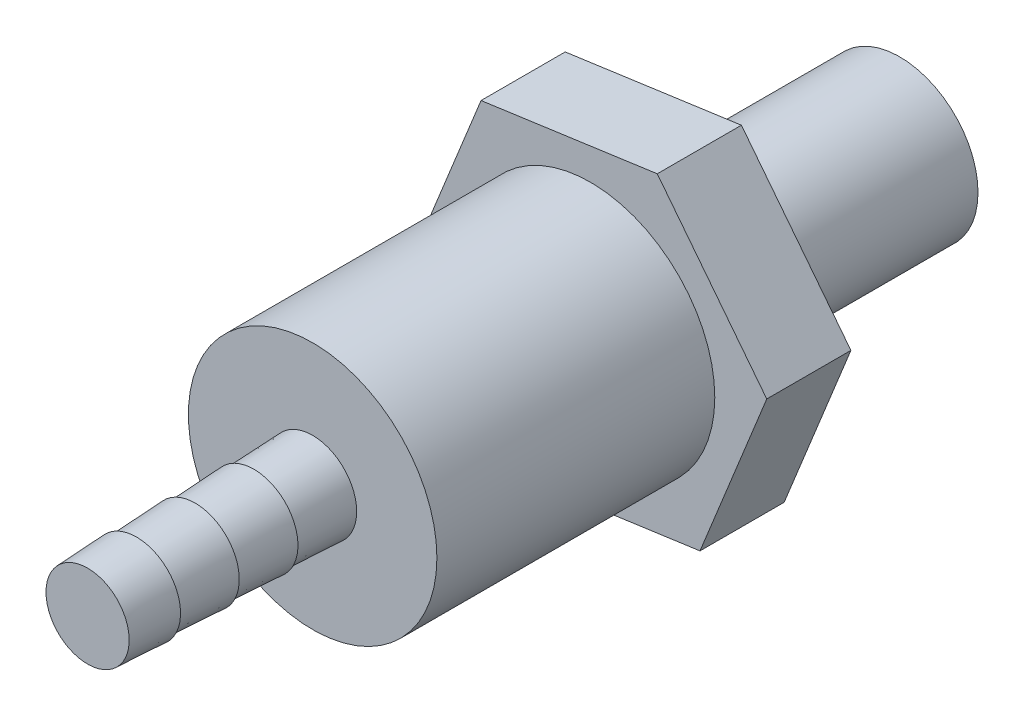
SolidWorks part; units mm, degrees
ref_plane "Face" through (0, 0, 0) normal (0, 0, 1) x (1, 0, 0)
ref_plane "Dessus" through (0, 0, 0) normal (0, 1, 0) x (1, 0, 0)
ref_plane "Droite" through (0, 0, 0) normal (1, 0, 0) x (0, 0, -1)
sketch "Esquisse1" plane through (0, 0, 0) normal (0, 0, 1) x (1, 0, 0)
  circle A0 centre (0, 0) radius 4
extrude "Extrusion1" add sketch "Esquisse1" along normal blind 11.5
sketch "Esquisse2" plane through (0, 0, 11.5) normal (0, 0, 1) x (1, 0, 0)
  line L1 (3.411, 8.4293) -> (-5.5945, 7.1687)
  line L2 (-5.5945, 7.1687) -> (-9.0055, -1.2606)
  line L3 (-9.0055, -1.2606) -> (-3.411, -8.4293)
  line L4 (-3.411, -8.4293) -> (5.5945, -7.1687)
  line L5 (5.5945, -7.1687) -> (9.0055, 1.2606)
  line L6 (9.0055, 1.2606) -> (3.411, 8.4293)
  circle A0 centre (0, 0) radius 7.875 construction
  dimension "D1" = 15.75
extrude "Extrusion2" add sketch "Esquisse2" along normal blind 4.3
sketch "Esquisse3" plane through (0, 0, 15.8) normal (0, 0, 1) x (1, 0, 0)
  circle A0 centre (0, 0) radius 6.35
extrude "Extrusion3" add sketch "Esquisse3" along normal blind 14.2
sketch "Esquisse4" plane through (0, 0, 0) normal (0, 1, 0) x (1, 0, 0)
  line L0 (0, -18.0768) -> (0, -49.0229) construction
  line L1 (0, -11.5) -> (0, 0) construction
  line L4 (0, -30) -> (0, -41.5)
  line L5 (-2.25, -30) -> (0, -30)
  line L6 (-2.25, -33) -> (-2.125, -33)
  line L7 (-2.25, -30) -> (-2.125, -33)
  line L8 (-2.25, -33) -> (-2.1, -36)
  line L10 (-2.25, -36) -> (-2.1, -36)
  line L11 (-2.25, -36) -> (-2.1, -39)
  line L13 (-2.25, -39) -> (-2.1, -39)
  line L14 (-2.25, -39) -> (-2.125, -41.5)
  line L15 (-2.125, -41.5) -> (0, -41.5)
revolve "Révolution4" add sketch "Esquisse4" angle 360 about L0
